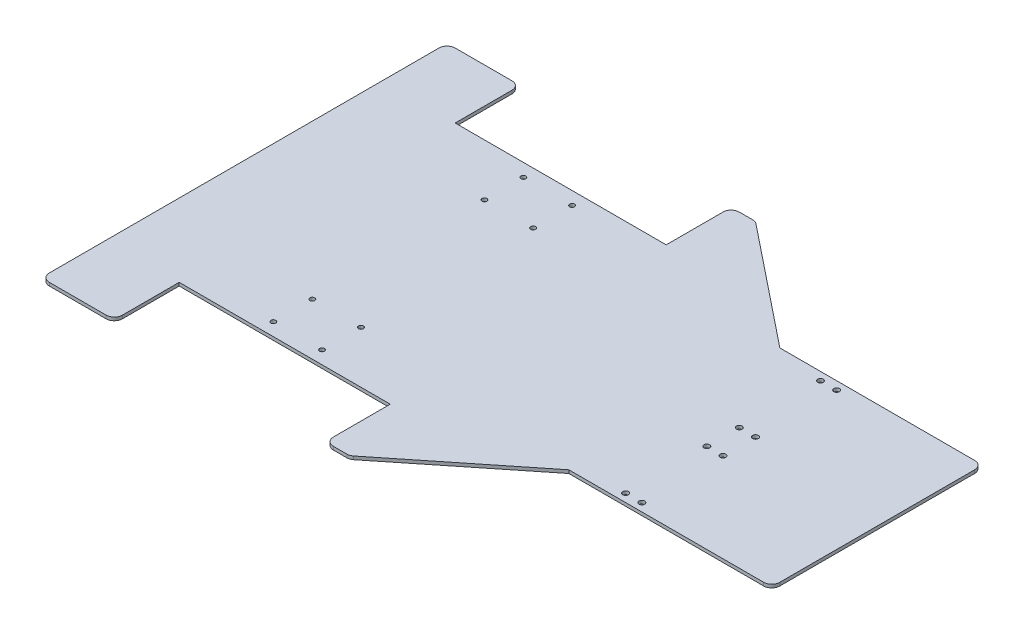
SolidWorks part; units mm, degrees
ref_plane "정면" through (0, 0, 0) normal (0, 0, 1) x (1, 0, 0)
ref_plane "윗면" through (0, 0, 0) normal (0, 1, 0) x (1, 0, 0)
ref_plane "우측면" through (0, 0, 0) normal (1, 0, 0) x (0, 0, -1)
sketch "스케치1" plane through (0, 0, 0) normal (0, 1, 0) x (1, 0, 0)
  line L1 (-195, -125) -> (195, -125)
  line L2 (-195, -125) -> (-195, 125)
  line L3 (-195, 125) -> (195, 125)
  line L4 (195, -125) -> (195, 125)
  line L5 (-195, -125) -> (195, 125) construction
  line L6 (-195, 125) -> (195, -125) construction
  point P0 (0, 0)
  dimension "D1" = 390
  dimension "D2" = 250
extrude "보스-돌출1" add sketch "스케치1" along normal blind 2
sketch "스케치2" plane through (0, 2, 0) normal (0, 1, 0) x (1, 0, 0)
  line L5 (195, 125) -> (-195, 125) construction
  line L6 (-150, 125) -> (-20, 125)
  line L7 (-150, 125) -> (-150, 85)
  line L8 (-150, 85) -> (-20, 85)
  line L9 (-20, 125) -> (-20, 85)
  line L10 (-150, -125) -> (-20, -125)
  line L11 (-150, -125) -> (-150, -85)
  line L12 (-150, -85) -> (-20, -85)
  line L13 (-20, -125) -> (-20, -85)
  line L14 (-195, -125) -> (195, -125) construction
  line L15 (70, 125) -> (195, 125)
  line L16 (70, 125) -> (70, 65)
  line L17 (70, 65) -> (195, 65)
  line L18 (195, 125) -> (195, 65)
  line L19 (70, -125) -> (195, -125)
  line L20 (70, -125) -> (70, -65)
  line L21 (70, -65) -> (195, -65)
  line L22 (195, -125) -> (195, -65)
  line L23 (195, -125) -> (195, 125) construction
  line L24 (-195, 125) -> (-195, -125) construction
  dimension "D1" = 130
  dimension "D2" = 40
  dimension "D3" = 40
  dimension "D4" = 60
  dimension "D5" = 60
  dimension "D6" = 45
  dimension "D7" = 125
extrude "컷-돌출1" cut sketch "스케치2" against normal blind 5
sketch "스케치3" plane through (0, 2, 0) normal (0, 1, 0) x (1, 0, 0)
  line L0 (-5, 125) -> (70, 65)
  line L2 (70, -65) -> (-5, -125)
  line L4 (-5, 125) -> (70, 125)
  line L5 (-5, -125) -> (70, -125)
  line L6 (70, -65) -> (70, -125)
  line L7 (70, 65) -> (70, 125)
  dimension "D1" = 75
  dimension "D2" = 75
extrude "컷-돌출2" cut sketch "스케치3" against normal blind 10
fillet "필렛1" radius 5 10 edges at (-20, 1, 125) (-20, 1, -125) (-5, 1, 125) (-5, 1, -125) (195, 1, -65) (195, 1, 65) (-195, 1, -125) (-195, 1, 125) (-150, 1, -125) (-150, 1, 125)
sketch "스케치4" plane through (0, 2, 0) normal (0, 1, 0) x (1, 0, 0)
  line L0 (-195, 0) -> (195, 0) construction
  line L1 (-100, 77) -> (-70, 77) construction
  line L2 (-100, 77) -> (-100, 53) construction
  line L3 (-100, 53) -> (-70, 53) construction
  line L4 (-70, 77) -> (-70, 53) construction
  line L5 (-100, 77) -> (-70, 53) construction
  line L6 (-100, 53) -> (-70, 77) construction
  line L7 (-195, 120) -> (-195, -120) construction
  line L8 (195, -60) -> (195, 60) construction
  line L9 (-150, 85) -> (-20, 85) construction
  line L10 (-100, -53) -> (-70, -77) construction
  line L11 (-100, -77) -> (-70, -53) construction
  line L12 (-70, -77) -> (-70, -53) construction
  line L13 (-100, -53) -> (-70, -53) construction
  line L14 (-100, -77) -> (-100, -53) construction
  line L15 (-100, -77) -> (-70, -77) construction
  line L17 (100, -60) -> (110, -60) construction
  line L18 (100, -60) -> (100, 60) construction
  line L19 (100, 60) -> (110, 60) construction
  line L20 (110, -60) -> (110, 60) construction
  line L21 (100, -60) -> (110, 60) construction
  line L22 (100, 60) -> (110, -60) construction
  line L23 (100, -10) -> (110, -10) construction
  line L24 (100, -10) -> (100, 10) construction
  line L25 (100, 10) -> (110, 10) construction
  line L26 (110, -10) -> (110, 10) construction
  line L27 (100, -10) -> (110, 10) construction
  line L28 (100, 10) -> (110, -10) construction
  circle A0 centre (-100, 77) radius 1.5
  circle A1 centre (-70, 77) radius 1.5
  circle A2 centre (-70, 53) radius 1.5
  circle A3 centre (-100, 53) radius 1.5
  circle A4 centre (-100, -53) radius 1.5
  circle A5 centre (-70, -53) radius 1.5
  circle A6 centre (-70, -77) radius 1.5
  circle A7 centre (-100, -77) radius 1.5
  circle A8 centre (100, 60) radius 1.75
  circle A9 centre (110, 60) radius 1.75
  circle A10 centre (100, 10) radius 1.75
  circle A11 centre (110, 10) radius 1.75
  circle A12 centre (100, -10) radius 1.75
  circle A13 centre (110, -10) radius 1.75
  circle A14 centre (100, -60) radius 1.75
  circle A15 centre (110, -60) radius 1.75
  point P0 (-85, 65)
  point P25 (-85, -65)
  point P26 (105, 0)
  point P31 (105, 0)
  dimension "D5" = 3
  dimension "D9" = 3.5
  dimension "D1" = 30
  dimension "D2" = 24
  dimension "D3" = 95
  dimension "D4" = 32
  dimension "D6" = 120
  dimension "D7" = 10
  dimension "D8" = 20
  dimension "D10" = 85
extrude "컷-돌출3" cut sketch "스케치4" against normal through all
